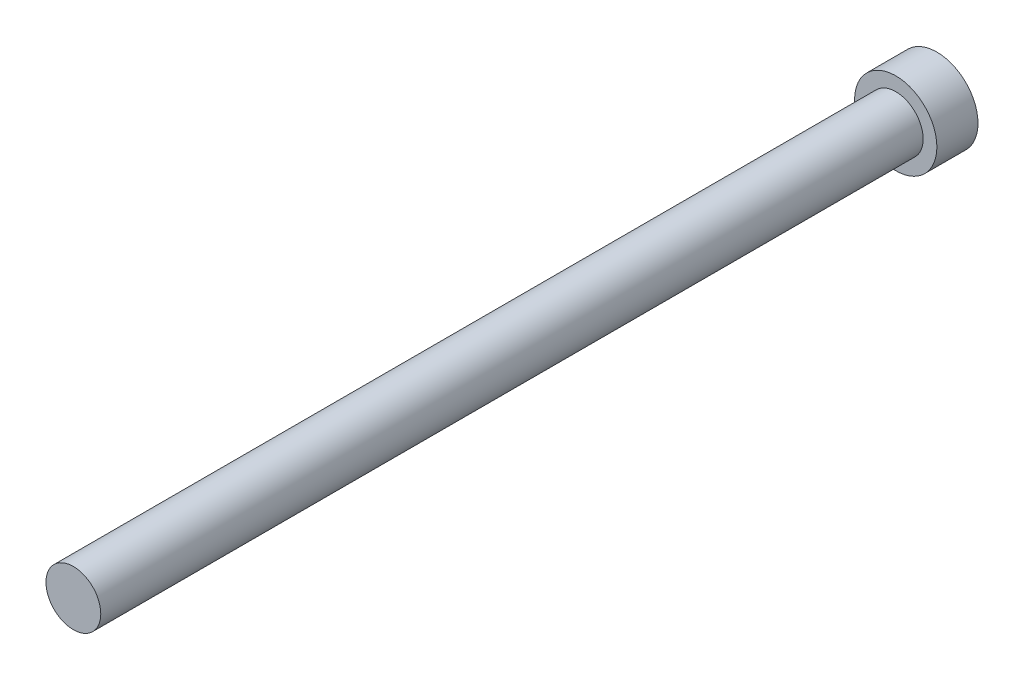
SolidWorks part; units mm, degrees
ref_plane "前视基准面" through (0, 0, 0) normal (0, 0, 1) x (1, 0, 0)
ref_plane "上视基准面" through (0, 0, 0) normal (0, 1, 0) x (1, 0, 0)
ref_plane "右视基准面" through (0, 0, 0) normal (1, 0, 0) x (0, 0, -1)
sketch "草图1" plane through (0, 0, 0) normal (0, 0, 1) x (1, 0, 0)
  line L1 (3.4641, 0) -> (1.7321, 3)
  line L2 (1.7321, 3) -> (-1.7321, 3)
  line L3 (-1.7321, 3) -> (-3.4641, 0)
  line L4 (-3.4641, 0) -> (-1.7321, -3)
  line L5 (-1.7321, -3) -> (1.7321, -3)
  line L6 (1.7321, -3) -> (3.4641, 0)
  circle A0 centre (0, 0) radius 6
  circle A1 centre (0, 0) radius 3 construction
  dimension "D1" = 12
  dimension "D2" = 6
extrude "凸台-拉伸1" add sketch "草图1" along normal blind 6
sketch "草图2" plane through (0, 0, 6) normal (0, 0, 1) x (1, 0, 0)
  circle A0 centre (0, 0) radius 4
  dimension "D1" = 8
extrude "凸台-拉伸2" add sketch "草图2" along normal blind 120
